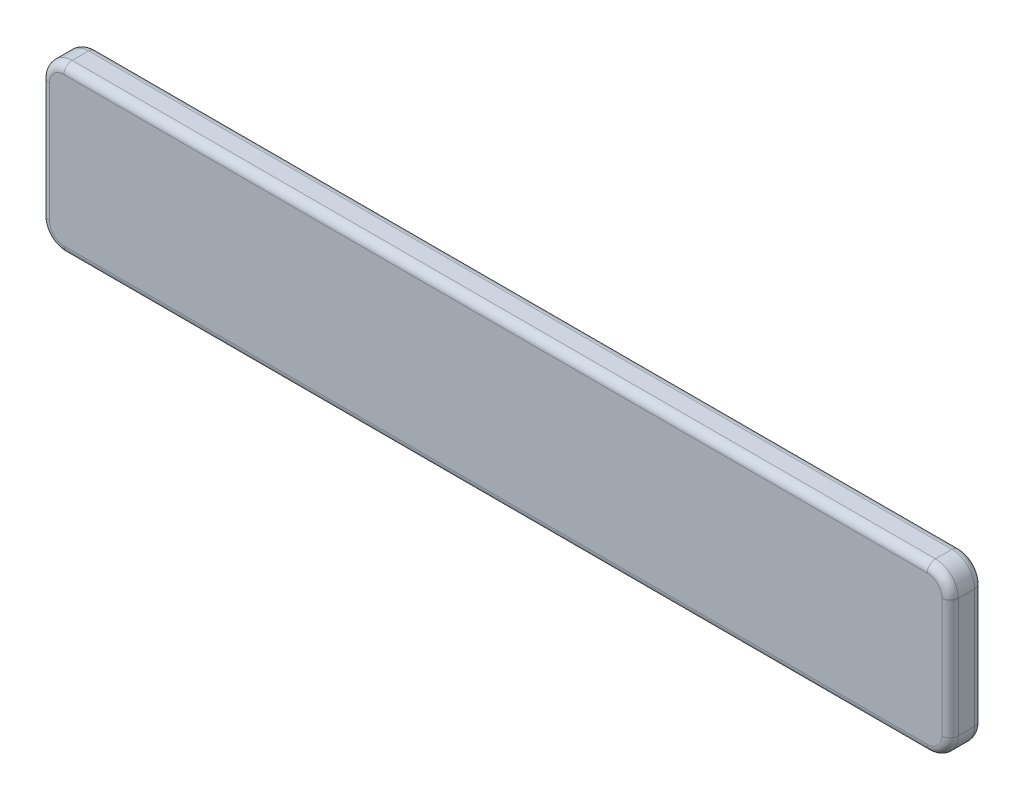
SolidWorks part; units mm, degrees
ref_plane "Front Plane" through (0, 0, 0) normal (0, 0, 1) x (1, 0, 0)
ref_plane "Top Plane" through (0, 0, 0) normal (0, 1, 0) x (1, 0, 0)
ref_plane "Right Plane" through (0, 0, 0) normal (1, 0, 0) x (0, 0, -1)
sketch "Sketch1" plane through (0, 0, 0) normal (0, 0, 1) x (1, 0, 0)
  line L0 (-157.3022, -51.2318) -> (-167.513, -51.2318) construction
  line L1 (-170.0022, -48.7426) -> (-170.0022, -2.4892) construction
  line L2 (-167.513, 0) -> (167.513, 0) construction
  line L3 (170.0022, -2.4892) -> (170.0022, -48.7426) construction
  line L4 (167.513, -51.2318) -> (157.3022, -51.2318) construction
  line L5 (-157.3022, -51.2318) -> (-167.513, -51.2318)
  line L6 (-170.0022, -48.7426) -> (-170.0022, -2.4892)
  line L7 (-167.513, 0) -> (167.513, 0)
  line L8 (170.0022, -2.4892) -> (170.0022, -48.7426)
  line L9 (167.513, -51.2318) -> (157.3022, -51.2318)
  line L10 (-157.3022, -51.2318) -> (157.3022, -51.2318)
  line L11 (-157.3022, -57.5818) -> (157.3022, -57.5818)
  line L12 (167.513, -57.5818) -> (157.3022, -57.5818)
  line L13 (176.3522, -2.4892) -> (176.3522, -48.7426)
  line L14 (-167.513, 6.35) -> (167.513, 6.35)
  line L15 (-176.3522, -48.7426) -> (-176.3522, -2.4892)
  line L16 (-157.3022, -57.5818) -> (-167.513, -57.5818)
  arc A0 (-170.0022, -48.7426) -> (-167.513, -51.2318) centre (-167.513, -48.7426) ccw construction
  arc A1 (-167.513, 0) -> (-170.0022, -2.4892) centre (-167.513, -2.4892) ccw construction
  arc A2 (170.0022, -2.4892) -> (167.513, 0) centre (167.513, -2.4892) ccw construction
  arc A3 (167.513, -51.2318) -> (170.0022, -48.7426) centre (167.513, -48.7426) ccw construction
  arc A4 (-170.0022, -48.7426) -> (-167.513, -51.2318) centre (-167.513, -48.7426) ccw
  arc A5 (-167.513, 0) -> (-170.0022, -2.4892) centre (-167.513, -2.4892) ccw
  arc A6 (170.0022, -2.4892) -> (167.513, 0) centre (167.513, -2.4892) ccw
  arc A7 (167.513, -51.2318) -> (170.0022, -48.7426) centre (167.513, -48.7426) ccw
  arc A8 (167.513, -57.5818) -> (176.3522, -48.7426) centre (167.513, -48.7426) ccw
  arc A9 (176.3522, -2.4892) -> (167.513, 6.35) centre (167.513, -2.4892) ccw
  arc A10 (-167.513, 6.35) -> (-176.3522, -2.4892) centre (-167.513, -2.4892) ccw
  arc A11 (-176.3522, -48.7426) -> (-167.513, -57.5818) centre (-167.513, -48.7426) ccw
  dimension "D1" = 6.35
extrude "Boss-Extrude1" add sketch "Sketch1" along normal blind 12.7 contours L16 A11 L15 A10 L14 A9 L13 A8 L12 L11
fillet "Fillet1" radius 3.175 8 edges at (-173.7633, 3.7611, 12.7) (-176.3522, -25.6159, 12.7) (-173.7633, -54.9929, 12.7) (0, -57.5818, 12.7) (173.7633, -54.9929, 12.7) (176.3522, -25.6159, 12.7) (173.7633, 3.7611, 12.7) (0, 6.35, 12.7)
fillet "Fillet2" radius 3.175 8 edges at (-173.7633, 3.7611, 0) (-176.3522, -25.6159, 0) (-173.7633, -54.9929, 0) (0, -57.5818, 0) (173.7633, -54.9929, 0) (176.3522, -25.6159, 0) (173.7633, 3.7611, 0) (0, 6.35, 0)
